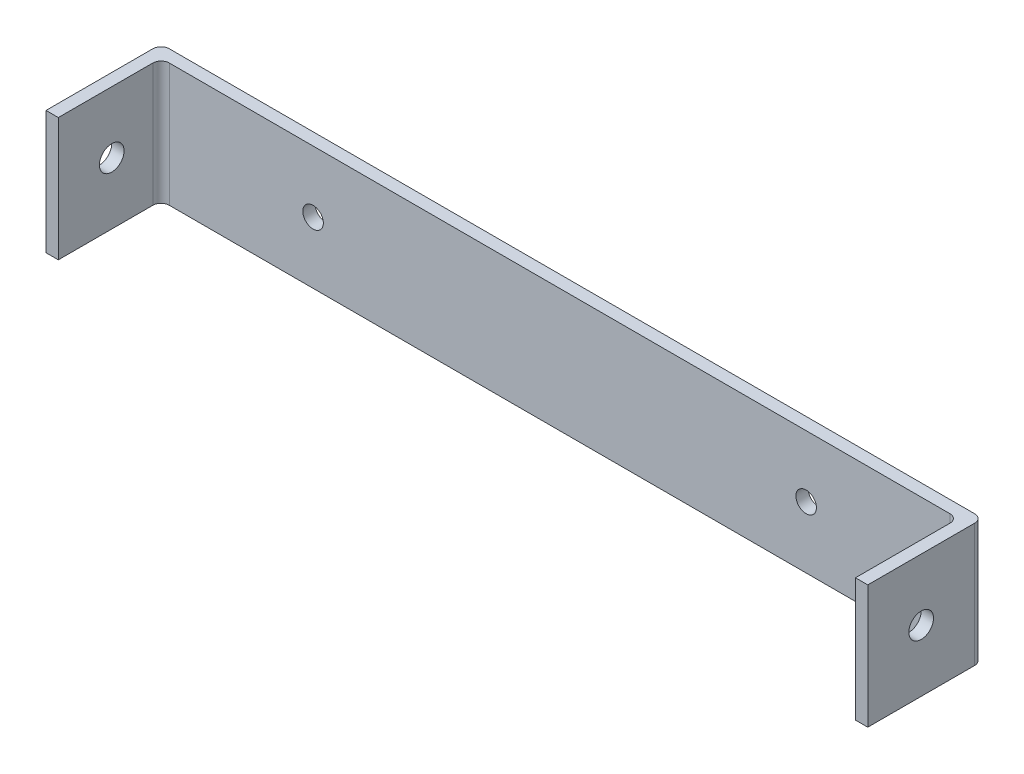
SolidWorks part; units mm, degrees
ref_plane "Plan de face" through (0, 0, 0) normal (0, 0, 1) x (1, 0, 0)
ref_plane "Plan de dessus" through (0, 0, 0) normal (0, 1, 0) x (1, 0, 0)
ref_plane "Plan de droite" through (0, 0, 0) normal (1, 0, 0) x (0, 0, -1)
sketch "Esquisse1" plane through (0, 0, 0) normal (0, 0, 1) x (1, 0, 0)
  line L1 (0, 0) -> (200, 0)
  line L2 (0, 0) -> (0, -30)
  line L3 (0, -30) -> (200, -30)
  line L4 (200, 0) -> (200, -30)
  circle A0 centre (40, -15) radius 2.5
  circle A1 centre (160, -15) radius 2.5
  dimension "D2" = 5
  dimension "D3" = 5
  dimension "D1" = 30
  dimension "D4" = 15
  dimension "D5" = 15
  dimension "D6" = 120
  dimension "D7" = 200
  dimension "D8" = 40
extrude "Boss.-Extru.1" add sketch "Esquisse1" along normal blind 3
sketch "Esquisse2" plane through (0, 0, 3) normal (0, 0, 1) x (1, 0, 0)
  line L0 (200, 0) -> (0, 0) construction
  line L1 (0, -30) -> (3, -30)
  line L2 (0, -30) -> (0, 0)
  line L3 (0, 0) -> (3, 0)
  line L4 (3, -30) -> (3, 0)
  line L5 (0, -30) -> (200, -30) construction
  line L6 (200, 0) -> (197, 0)
  line L7 (200, 0) -> (200, -30)
  line L8 (200, -30) -> (197, -30)
  line L9 (197, 0) -> (197, -30)
  point P14 (200, -15)
  dimension "D1" = 3
  dimension "D2" = 3
extrude "Boss.-Extru.2" add sketch "Esquisse2" along normal blind 25
sketch "Esquisse3" plane through (0, 0, 0) normal (-1, 0, 0) x (0, 0, 1)
  line L0 (28, 0) -> (0, 0) construction
  line L2 (0, 0) -> (0, -30) construction
  circle A0 centre (15, -15) radius 3
  dimension "D1" = 6
  dimension "D2" = 15
  dimension "D3" = 15
extrude "Enlèv. mat.-Extru.1" cut sketch "Esquisse3" against normal blind 229
fillet "Congé1" radius 2 4 edges at (200, -15, 0) (197, -15, 3) (0, -15, 0) (3, -15, 3)
